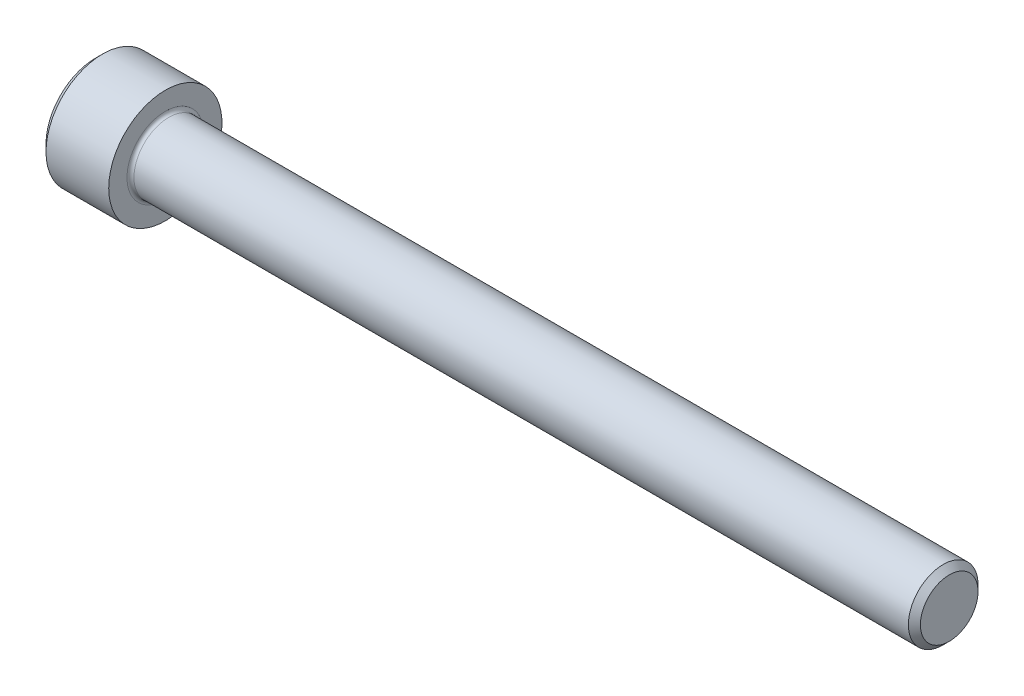
SolidWorks part; units mm, degrees
revolve "Base-Revolve" add sketch "BodySke"
sketch "BodySke" plane through (0, 0, 0) normal (0, 0, 1) x (1, 0, 0)
  line L0 (0, 0) -> (0, 5.7)
  line L1 (0.8, 6.5) -> (8, 6.5)
  line L2 (8, 6.5) -> (8, 4)
  line L3 (8, 4) -> (97.3095, 4)
  line L4 (98, 3.3095) -> (98, 0)
  line L5 (98, 0) -> (0, 0)
  line L6 (-31.75, 0) -> (127, 0) construction
  line L7 (0, 5.7) -> (0.8, 6.5)
  line L8 (98, 3.3095) -> (97.3095, 4)
  line L9 (0, -5.7) -> (0.8, -6.5) construction
  line L10 (98, -3.3095) -> (97.3095, -4) construction
  line L11 (9.25, 2.4825) -> (9.25, -3.8675) construction
  line L12 (70, 2.4825) -> (70, -3.8675) construction
  line L13 (48, 2.4825) -> (48, -3.8675) construction
  dimension "Diameter" = 8
  dimension "Head_ht" = 8
  dimension "Length" = 90
  dimension "Body_ch_ang" = 45
  dimension "Head_dia" = 13
  dimension "Head_ch_ang" = 45
  dimension "Minor_dia" = 6.619
  dimension "Advance" = 1.25
  dimension "Thread_nom" = 28
  dimension "Thread_length" = 50
  dimension "Head_ch_ht" = 0.8
cosmetic thread "ThreadCosmetic" [suppressed]
fillet "Fillet1" radius 0.4 1 edges at (8, 0, 4)
ref_plane "Plane1" through (0, 0, 0) normal (0, 0, 1) x (1, 0, 0)
ref_plane "Plane2" through (0, 0, 0) normal (0, 1, 0) x (1, 0, 0)
ref_plane "Plane3" through (0, 0, 0) normal (1, 0, 0) x (0, 0, -1)
other "Configuration Table"
sketch "Sketch2" plane through (0, 0, 0) normal (0, 0, 1) x (1, 0, 0)
  line L0 (0, 3.0475) -> (4, 3.0475)
  line L1 (4, 3.0475) -> (5.7595, 0)
  line L2 (-31.75, 0) -> (127, 0) construction
  line L3 (5.7595, 0) -> (0, 0)
  line L4 (0, 0) -> (0, 3.0475)
  line L5 (0, 5.7) -> (0, -5.7) construction
  line L6 (0, 0) -> (47.625, 0) construction
  line L7 (8, -6.5) -> (8, 6.5) construction
  dimension "D1" = 3.0475
  dimension "D2" = 60
revolve "Hex-PreBroach" cut sketch "Sketch2" angle 360 about L6
sketch "Sketch3" plane through (0, 0, 0) normal (-1, 0, 0) x (0, 0.5, 0.866)
  line L0 (1.7595, 3.0475) -> (-1.7595, 3.0475)
  line L1 (-1.7595, 3.0475) -> (-3.5189, 0)
  line L2 (1.7595, 3.0475) -> (3.5189, 0)
  line L3 (1.7595, -3.0475) -> (3.5189, 0)
  line L4 (1.7595, -3.0475) -> (-1.7595, -3.0475)
  line L5 (-1.7595, -3.0475) -> (-3.5189, 0)
  dimension "D1" = 3.0475
  dimension "D2" = 3.0475
  dimension "Hex_size" = 6.095
extrude "Hex" cut sketch "Sketch3" against normal blind 4
sketch "Sketch4" plane through (0, 0, 0) normal (-1, 0, 0) x (0, 0, 1)
  line L0 (0, 0) -> (3.7846, 0)
  line L1 (0, 0) -> (6.1484, 3.5498) construction
  line L2 (0, 0) -> (1.8923, 3.2776)
  line L3 (3.1235, 0.8061) -> (3.6229, 1.0945)
  line L4 (2.2599, 2.3019) -> (2.7593, 2.5903)
  arc A0 (3.1235, 0.8061) -> (2.2599, 2.3019) centre (0, 0) ccw
  arc A1 (3.7846, 0) -> (3.6229, 1.0945) centre (0, 0) ccw
  arc A2 (1.8923, 3.2776) -> (2.7593, 2.5903) centre (0, 0) cw
  dimension "D1" = 30
  dimension "D2" = 60
  dimension "Spline_p_dim" = 1.7272
  dimension "D3" = 0.8636
extrude "Spline" [suppressed] cut sketch "Sketch4" against normal blind 4
pattern_circular "CirPattern1" [suppressed] count 6 every 60
sketch "Sketch5" plane through (0, 0, 0) normal (0, 0, 1) x (1, 0, 0)
  line L0 (-31.75, 0) -> (127, 0) construction
  line L2 (0, 5.7) -> (0, -5.7) construction
  circle A0 centre (2.7, 0) radius 0.675
  dimension "Drilled_hole_dia" = 1.35
  dimension "Drilled_hole_loc" = 2.7
extrude "Hole" [suppressed] cut sketch "Sketch5" against normal through all and the other way through all
pattern_circular "Drilled-4" [suppressed] count 2 every 60
pattern_circular "Drilled-6" [suppressed] count 3 every 60
sketch "ThdSchSke" plane through (0, 0, 0) normal (0, 0, 1) x (1, 0, 0)
  line L0 (70, -3.3095) -> (69.5165, -4)
  line L1 (70, -3.3095) -> (70.4835, -4)
  line L2 (70.4835, -4) -> (70.4835, -5)
  line L3 (-3.175, 0) -> (5.1513, 0) construction
  line L5 (70.4835, -5) -> (69.5165, -5)
  line L6 (69.5165, -5) -> (69.5165, -4)
  line L7 (0, 5.7) -> (0, -5.7) construction
  dimension "Thread_minor" = 6.619
  dimension "Diameter" = 8
  dimension "Start" = 70
revolve "ThreadSchematic" [suppressed] cut sketch "ThdSchSke" angle 360 about L3
pattern_linear "ThdSchPat" [suppressed]
equation "\"D2@Sketch3\" = \"Hex_size@Sketch3\" / 2"
equation "\"D1@Sketch3\" = \"Hex_size@Sketch3\" / 2"
equation "\"D1@Sketch2\" = \"Hex_size@Sketch3\" / 2"
equation "\"D3@Sketch4\" = \"Spline_p_dim@Sketch4\" / 2"
equation "\"Thread_minor@ThreadCosmetic\"  =  \"Minor_dia@BodySke\""
equation "\"D2@CirPattern1\" = 360 / \"Num_teeth@CirPattern1\""
equation "\"Wall_thickness@Sketch2\" = \"Head_ht@BodySke\" - \"Key_eng@Hex\""
equation "\"Thread_length@ThreadCosmetic\" = ((sgn( (\"Length@BodySke\" - \"Advance@BodySke\" ) - \"Thread_nom@BodySke\" )-1)*( (\"Length@BodySke\" - \"Advance@BodySke\" ) - \"Thread_nom@BodySke\" ))/-2+ \"Thread_nom@BodySke\""
equation "\"Thread_minor@ThdSchSke\" = \"Minor_dia@BodySke\""
equation "\"Diameter@ThdSchSke\" = \"Diameter@BodySke\""
equation "\"Overcut@ThdSchSke\" = \"Diameter@BodySke\" * 1.25"
equation "\"Start@ThdSchSke\" = \"Head_ht@BodySke\" + \"Length@BodySke\" - \"Thread_length@ThreadCosmetic\"  '---Non-countersunk---"
equation "\"Num_threads@ThdSchPat\" = int( \"Thread_length@ThreadCosmetic\" / \"Advance@BodySke\" + 0.999 )  + 1"
equation "\"Advance@ThdSchPat\" = \"Thread_length@ThreadCosmetic\" /  (\"Num_threads@ThdSchPat\" - 1) 'relax it"
equation "\"Num_threads@ThdSchPat\" = \"Num_threads@ThdSchPat\" - sgn( \"Num_threads@ThdSchPat\" - 1) '---chamfered tips only---"
